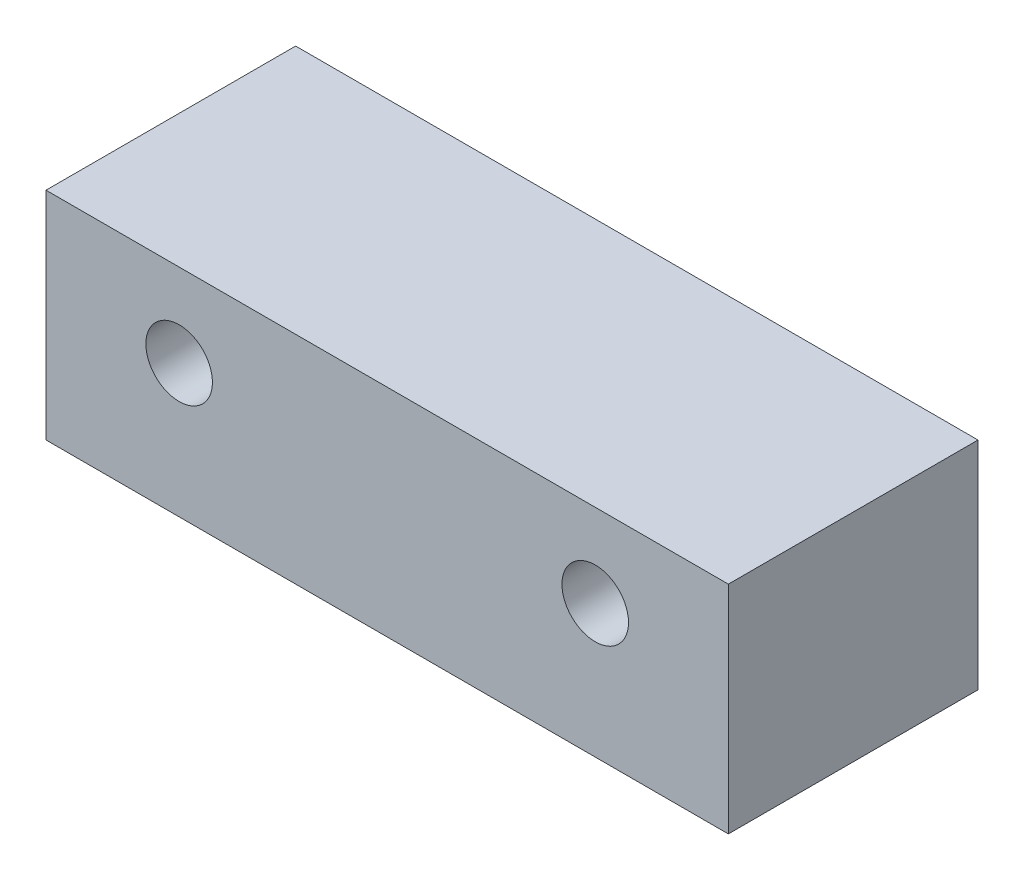
SolidWorks part; units mm, degrees
material "ABS"
ref_plane "前视基准面" through (0, 0, 0) normal (0, 0, 1) x (1, 0, 0)
ref_plane "上视基准面" through (0, 0, 0) normal (0, 1, 0) x (1, 0, 0)
ref_plane "右视基准面" through (0, 0, 0) normal (1, 0, 0) x (0, 0, -1)
other "Configuration Table"
sketch "草图1" plane through (0, 0, 0) normal (0, 0, 1) x (1, 0, 0)
  line L0 (0, 0) -> (12.5, 0) construction
  line L1 (-20.5, -5) -> (20.5, -5)
  line L2 (-20.5, -5) -> (-20.5, 5)
  line L3 (-20.5, 5) -> (20.5, 5)
  line L4 (20.5, -5) -> (20.5, 5)
  line L5 (-20.5, -5) -> (20.5, 5) construction
  line L6 (-20.5, 5) -> (20.5, -5) construction
  line L7 (0, 0) -> (0, 8.8) construction
  circle A0 centre (12.5, 0) radius 2
  circle A1 centre (-12.5, 0) radius 2
  point P0 (0, 0)
  dimension "D3" = 4
  dimension "D1" = 10
  dimension "D2" = 8
  dimension "D4" = 12.5
extrude "凸台-拉伸1" add sketch "草图1" along normal blind 15
sketch "草图2" plane through (0, 0, 15) normal (0, 0, 1) x (1, 0, 0)
  line L0 (20.5, -5) -> (20.5, 5) construction
  line L1 (-20.5, -5) -> (20.5, -5)
  line L2 (-20.5, -5) -> (-20.5, -8)
  line L3 (-20.5, -8) -> (20.5, -8)
  line L4 (20.5, -5) -> (20.5, -8)
  dimension "D1" = 3
extrude "凸台-拉伸2" add sketch "草图2" against normal up to surface (15 mm away) up to face at (14.5, 0, 0)
